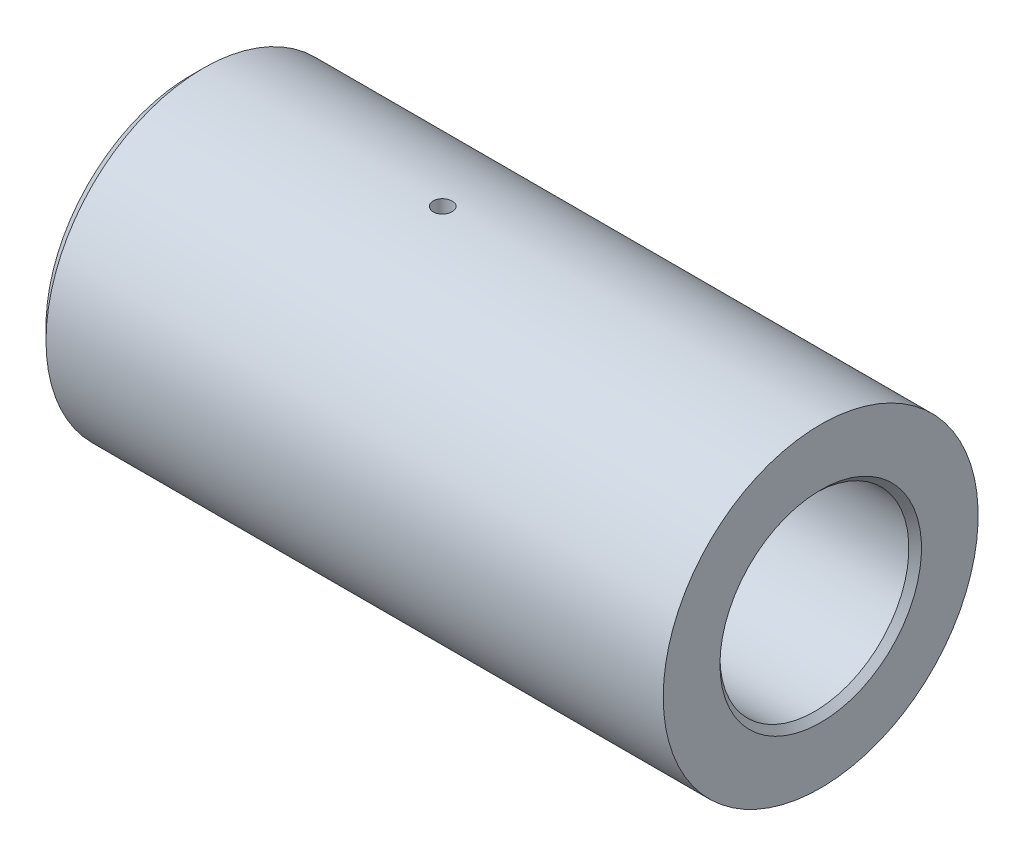
SolidWorks part; units mm, degrees
ref_plane "Piano frontale" through (0, 0, 0) normal (0, 0, 1) x (1, 0, 0)
ref_plane "Piano superiore" through (0, 0, 0) normal (0, 1, 0) x (1, 0, 0)
ref_plane "Piano destro" through (0, 0, 0) normal (1, 0, 0) x (0, 0, -1)
sketch "Schizzo2" plane through (0, 0, 0) normal (0, 0, 1) x (1, 0, 0)
  line L0 (0, 0) -> (49.4688, 0) construction
  line L1 (0, 10) -> (0, 25)
  line L2 (0, 25) -> (100, 25)
  line L3 (100, 25) -> (100, 15)
  line L4 (100, 15) -> (65, 15)
  line L5 (65, 15) -> (65, 18)
  line L6 (65, 18) -> (60, 18)
  line L7 (60, 18) -> (60, 15)
  line L8 (60, 15) -> (25, 15)
  line L9 (25, 15) -> (25, 10)
  line L10 (25, 10) -> (0, 10)
  line L11 (0, 10) -> (0, 0) construction
  line L12 (60, 15) -> (65, 15) construction
  dimension "D1" = 50
  dimension "D2" = 20
  dimension "D3" = 30
  dimension "D4" = 36
  dimension "D5" = 40
  dimension "D6" = 75
  dimension "D7" = 5
  dimension "D8" = 100
revolve "Rivoluzione1" add sketch "Schizzo2" angle 360 about L0
fillet "Raccordo1" radius 3 1 edges at (25, 0, 15)
chamfer "Smusso1" distance 2 angle 45 1 edges at (0, 0, 25)
chamfer "Smusso2" distance 1 angle 45 2 edges at (100, 0, 15) (0, 0, 10)
ref_plane "Piano1" through (0, 25, 0) normal (0, 1, 0) x (1, 0, 0)
hole_wizard "Foro Ø3.0 (3)-1" positions "Schizzo9" profile "Schizzo10" hole size "Ø3.0" standard "ISO" end condition through all
sketch "Schizzo9" plane through (0, 25, 0) normal (0, 1, 0) x (1, 0, 0)
  line L0 (0, 0) -> (40, 0) construction
  point P0 (40, 0)
  dimension "D1" = 40
sketch "Schizzo10" plane through (40, 25, 0) normal (1, 0, 0) x (0, 0, 1)
  line L0 (0, 0) -> (0, 50)
  line L1 (0, 50) -> (1.5, 50)
  line L2 (1.5, 50) -> (1.5, 0)
  line L5 (1.5, 0) -> (0, 0)
  line L11 (0, -6.35) -> (0, 107.95) construction
  dimension "Thru Hole Dia." = 3
  dimension "Thru Hole Depth" = 50
